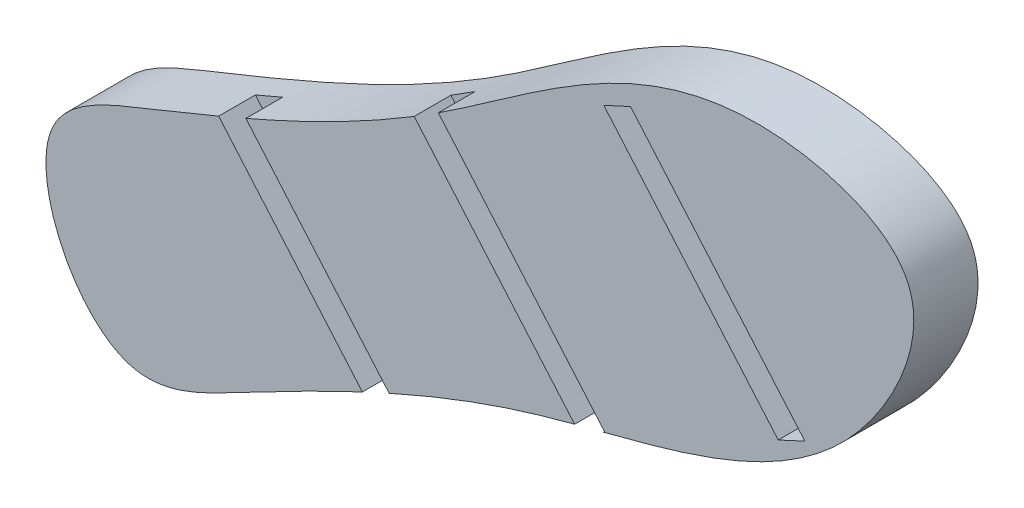
SolidWorks part; units mm, degrees
material "Caucho"
ref_plane "Alzado" through (0, 0, 0) normal (0, 0, 1) x (1, 0, 0)
ref_plane "Planta" through (0, 0, 0) normal (0, 1, 0) x (1, 0, 0)
ref_plane "Vista lateral" through (0, 0, 0) normal (1, 0, 0) x (0, 0, -1)
ref_plane "Plano_goma" through (0, 0, 12.5) normal (0, 0, 1) x (1, 0, 0)
sketch "Sk_Goma" plane through (0, 0, 0) normal (0, 0, 1) x (1, 0, 0)
  spline S0 degree 3 poles (434.3863, 332.3422) (428.9443, 344.1331) (441.1466, 348.8882) (453.6205, 354.2888) (465.9627, 365.6031) (480.5578, 360.8034) (474.7412, 346.583) (458.1239, 344.5314) (445.9213, 338.5429) (434.3863, 332.3422) (428.9443, 344.1331) (441.1466, 348.8882) knots -0.299528 -0.141321 -0.087871 0 0.05345 0.211657 0.387435 0.456064 0.524694 0.700472 0.858679 0.912129 1 1.05345 1.211657 1.387435 only from (431.735, 343.7767) to (431.735, 343.7767)
extrude "Goma" add sketch "Sk_Goma" along normal blind 3.5 from offset 12.5
sketch "Sk_Ranuras_agua" plane through (0, 0, 12.5) normal (0, 0, 1) x (1, 0, 0)
  line L0 (439.9765, 349.7832) -> (441.4292, 350.4537)
  line L1 (441.4292, 350.4537) -> (450.9278, 339.4185)
  line L2 (450.9278, 339.4185) -> (449.4751, 338.748)
  line L3 (449.4751, 338.748) -> (439.9765, 349.7832)
  line L4 (450.872, 354.8119) -> (452.3247, 355.4824)
  line L5 (452.3247, 355.4824) -> (461.8234, 344.4472)
  line L6 (461.8234, 344.4472) -> (460.3706, 343.7767)
  line L7 (460.3706, 343.7767) -> (450.872, 354.8119)
  line L8 (461.7675, 359.8406) -> (463.2202, 360.5111)
  line L9 (463.2202, 360.5111) -> (472.7189, 349.4759)
  line L10 (472.7189, 349.4759) -> (471.2661, 348.8054)
  line L11 (471.2661, 348.8054) -> (461.7675, 359.8406)
extrude "Ranuras_agua" cut sketch "Sk_Ranuras_agua" along normal blind 2
mirror "Simetria_lado_izq" about plane through (0, 0, 0) normal (0, 0, 1) of bodies 102
delete or keep bodies "Borrar_original_dcho" type delete bodies bodies 102
